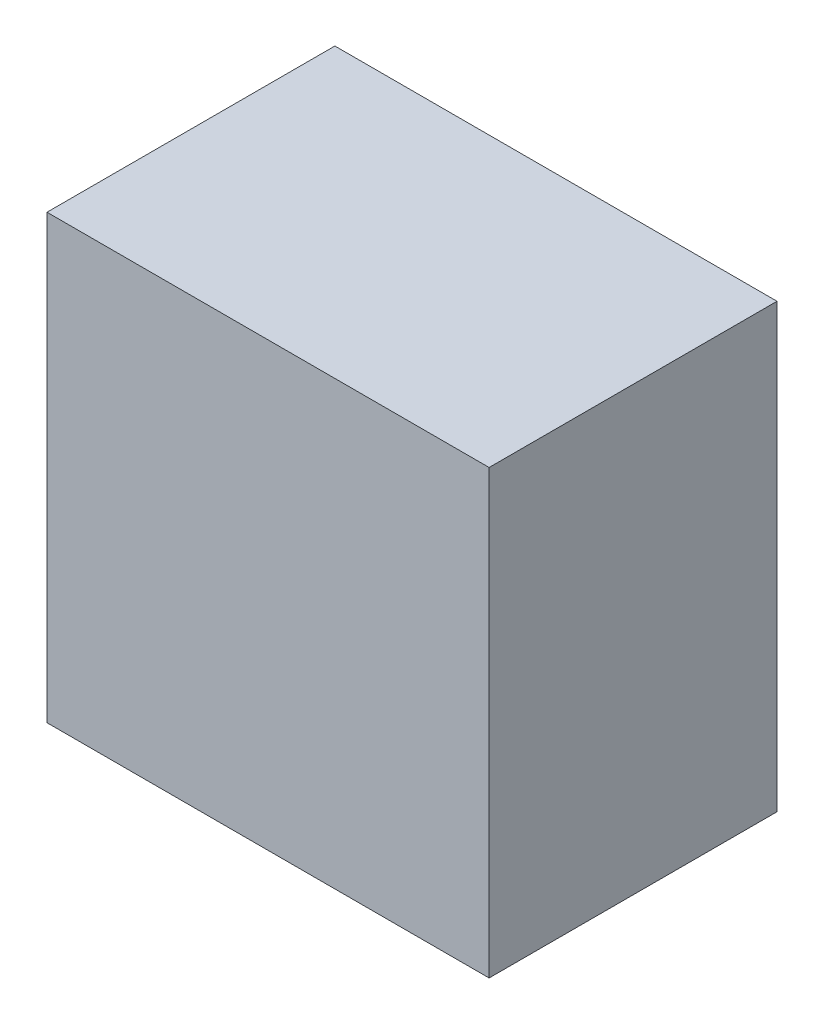
SolidWorks part; units mm, degrees
ref_plane "Спереди" through (0, 0, 0) normal (0, 0, 1) x (1, 0, 0)
ref_plane "Сверху" through (0, 0, 0) normal (0, 1, 0) x (1, 0, 0)
ref_plane "Справа" through (0, 0, 0) normal (1, 0, 0) x (0, 0, -1)
sketch "Эскиз1" plane through (0, 0, 0) normal (0, 0, 1) x (1, 0, 0)
  line L1 (21.5, 21.5) -> (-21.5, 21.5)
  line L2 (21.5, 21.5) -> (21.5, -21.5)
  line L3 (21.5, -21.5) -> (-21.5, -21.5)
  line L4 (-21.5, 21.5) -> (-21.5, -21.5)
  line L5 (21.5, 21.5) -> (-21.5, -21.5) construction
  line L6 (21.5, -21.5) -> (-21.5, 21.5) construction
  point P0 (0, 0)
  dimension "D1" = 43
  dimension "D2" = 43
extrude "Бобышка-Вытянуть1" add sketch "Эскиз1" along normal blind 28
sketch "Эскиз2" plane through (0, 0, 0) normal (0, 0, -1) x (-1, 0, 0)
  circle A0 centre (0, 0) radius 4.05
extrude "Вырез-Вытянуть1" cut sketch "Эскиз2" against normal blind 12
